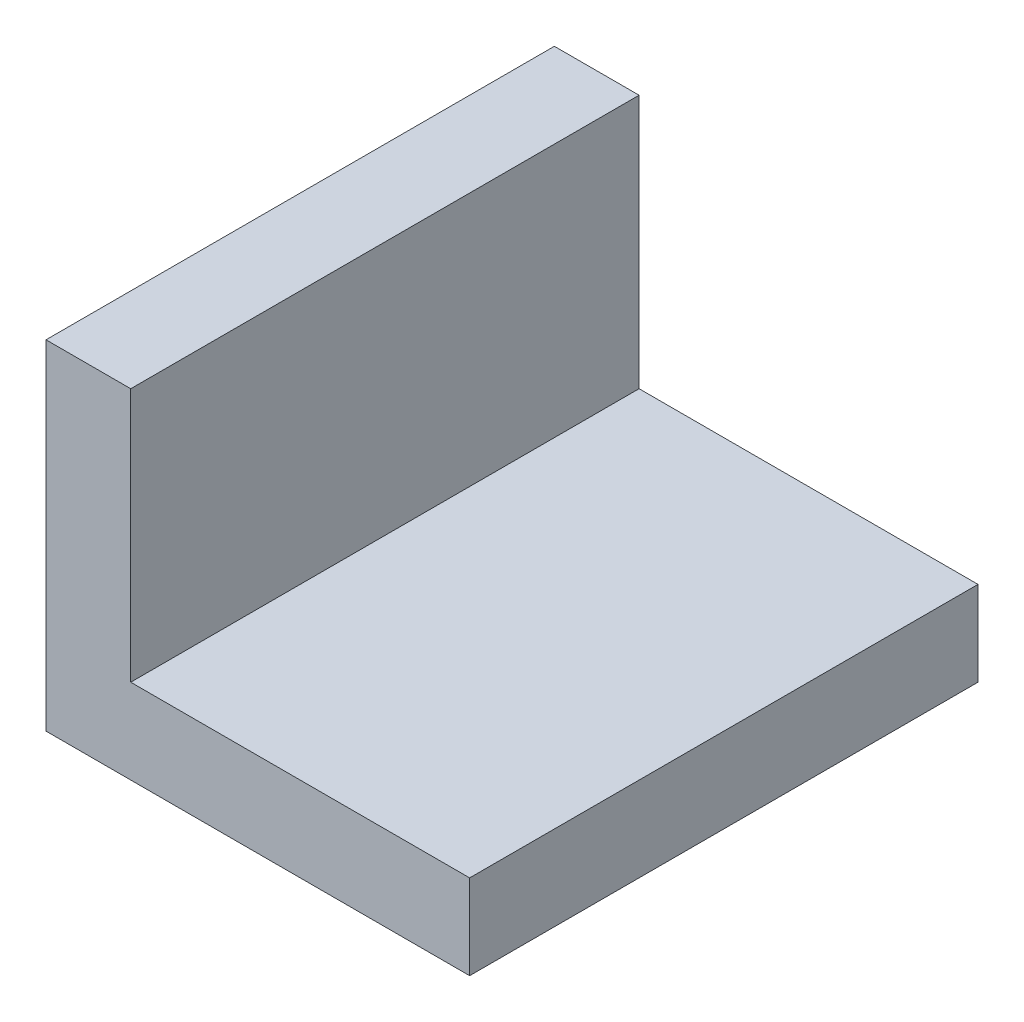
SolidWorks part; units mm, degrees
material "3.0255 (EN AW-1350A)"
ref_plane "Plan de face" through (0, 0, 0) normal (0, 0, 1) x (1, 0, 0)
ref_plane "Plan de dessus" through (0, 0, 0) normal (0, 1, 0) x (1, 0, 0)
ref_plane "Plan de droite" through (0, 0, 0) normal (1, 0, 0) x (0, 0, -1)
sketch "Esquisse1" plane through (0, 0, 0) normal (0, 0, 1) x (1, 0, 0)
  line L0 (0, 12) -> (0, 0)
  line L1 (0, 0) -> (15, 0)
  line L2 (15, 0) -> (15, 3)
  line L3 (15, 3) -> (3, 3)
  line L4 (3, 3) -> (3, 12)
  line L5 (3, 12) -> (0, 12)
  dimension "D1" = 3
  dimension "D2" = 3
  dimension "D3" = 15
  dimension "D4" = 12
extrude "Boss.-Extru.1" add sketch "Esquisse1" along normal blind 18
